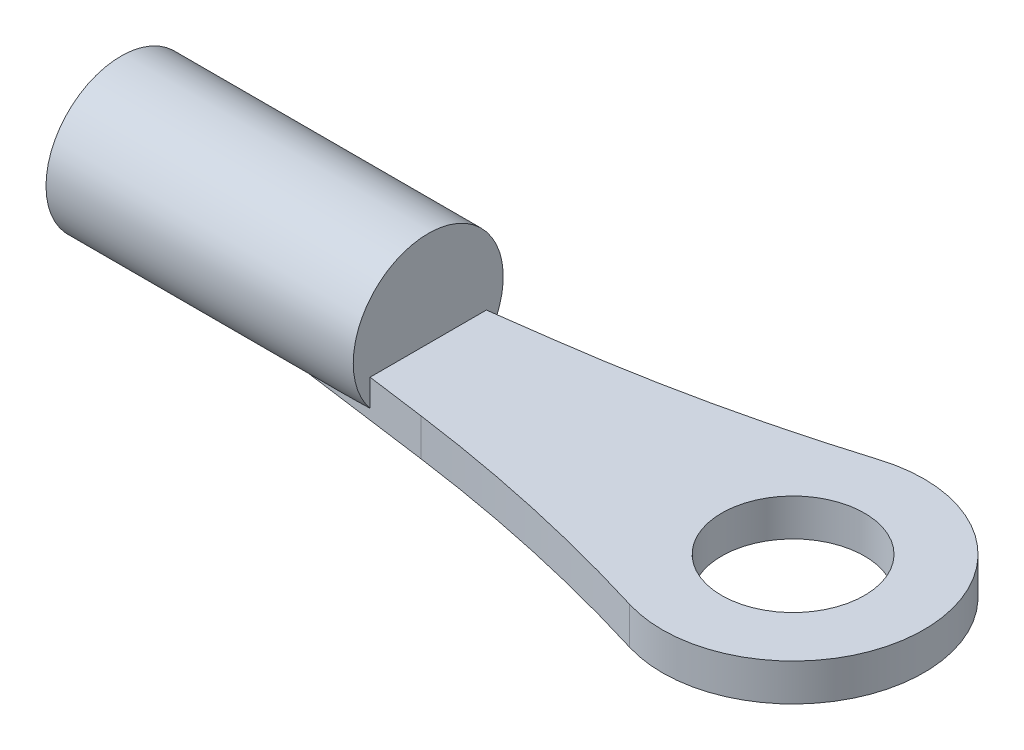
SolidWorks part; units mm, degrees
ref_plane "Front Plane" through (0, 0, 0) normal (0, 0, 1) x (1, 0, 0)
ref_plane "Top Plane" through (0, 0, 0) normal (0, 1, 0) x (1, 0, 0)
ref_plane "Right Plane" through (0, 0, 0) normal (1, 0, 0) x (0, 0, -1)
sketch "Sketch1" plane through (0, 0, 0) normal (0, 1, 0) x (1, 0, 0)
  line L0 (-6.4687, -1.4013) -> (-9.3011, -1.016)
  line L1 (-14.224, 0) -> (-14.224, 1.016)
  line L2 (-14.224, 0) -> (-14.224, -1.016)
  line L3 (-14.224, 1.016) -> (-9.3011, 1.016)
  line L4 (-14.224, -1.016) -> (-9.3011, -1.016)
  line L5 (-9.3011, 1.016) -> (-6.4687, 1.4013)
  circle A0 centre (0, 0) radius 1.5113
  arc A1 (-0.8135, -2.6464) -> (-0.8135, 2.6464) centre (0, 0) ccw
  arc A2 (-0.8135, 2.6464) -> (-6.4687, 1.4013) centre (-11.2618, 36.6368) cw
  arc A3 (-0.8135, -2.6464) -> (-6.4687, -1.4013) centre (-11.2618, -36.6368) ccw
  dimension "D1" = 3.0226
  dimension "D2" = 5.5372
  dimension "D6" = 35.56
  dimension "D3" = 14.224
  dimension "D4" = 1.016
  dimension "D5" = 1.016
extrude "Boss-Extrude1" add sketch "Sketch1" along normal blind 0.7874
sketch "Sketch2" plane through (-14.224, 0, 0) normal (-1, 0, 0) x (0, 0, 1)
  circle A0 centre (0, 1.2198) radius 1.5875
  dimension "D1" = 3.175
extrude "Boss-Extrude2" add sketch "Sketch2" against normal blind 6.5024
sketch "Sketch3" plane through (-14.224, 0, 0) normal (-1, 0, 0) x (0, 0, 1)
  circle A0 centre (0, 1.2198) radius 1.1185
extrude "Cut-Extrude1" cut sketch "Sketch3" against normal blind 2.54
